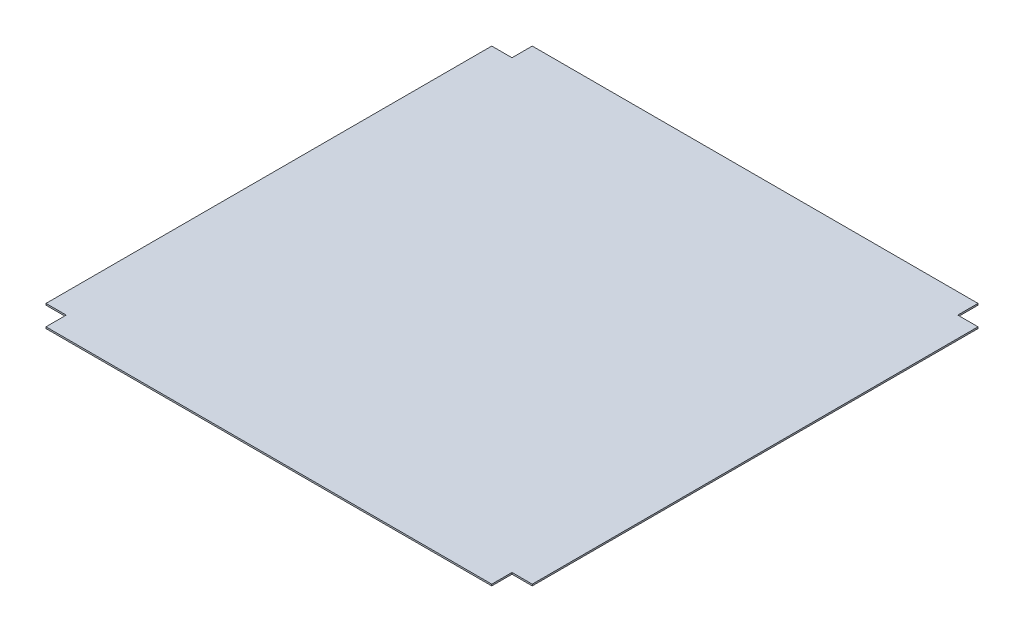
SolidWorks part; units mm, degrees
ref_plane "Front Plane" through (0, 0, 0) normal (0, 0, 1) x (1, 0, 0)
ref_plane "Top Plane" through (0, 0, 0) normal (0, 1, 0) x (1, 0, 0)
ref_plane "Right Plane" through (0, 0, 0) normal (1, 0, 0) x (0, 0, -1)
sketch "Sketch1" plane through (0, 0, 0) normal (0, 1, 0) x (1, 0, 0)
  line L1 (-609.6, -609.6) -> (609.6, -609.6)
  line L2 (-609.6, -609.6) -> (-609.6, 609.6)
  line L3 (-609.6, 609.6) -> (609.6, 609.6)
  line L4 (609.6, -609.6) -> (609.6, 609.6)
  line L5 (-609.6, -609.6) -> (609.6, 609.6) construction
  line L6 (-609.6, 609.6) -> (609.6, -609.6) construction
  point P0 (0, 0)
  dimension "D2" = 1219.2
  dimension "D1" = 1219.2
extrude "Boss-Extrude1" add sketch "Sketch1" along normal mid plane 4
sketch "Sketch2" plane through (0, 2, 0) normal (0, 1, 0) x (1, 0, 0)
  line L0 (0, 609.6) -> (0, -609.6) construction
  line L1 (-609.6, 609.6) -> (-558.8, 609.6)
  line L2 (-609.6, 609.6) -> (-609.6, 558.8)
  line L3 (-609.6, 558.8) -> (-558.8, 558.8)
  line L4 (-558.8, 609.6) -> (-558.8, 558.8)
  line L5 (609.6, 609.6) -> (-609.6, 609.6) construction
  line L6 (-609.6, -609.6) -> (609.6, -609.6) construction
  line L7 (609.6, 0) -> (-609.6, 0) construction
  line L8 (609.6, -609.6) -> (609.6, 609.6) construction
  line L9 (-609.6, 609.6) -> (-609.6, -609.6) construction
  line L10 (558.8, 609.6) -> (558.8, 558.8)
  line L11 (609.6, 558.8) -> (558.8, 558.8)
  line L12 (609.6, 609.6) -> (609.6, 558.8)
  line L13 (609.6, 609.6) -> (558.8, 609.6)
  line L14 (609.6, -609.6) -> (558.8, -609.6)
  line L15 (609.6, -609.6) -> (609.6, -558.8)
  line L16 (609.6, -558.8) -> (558.8, -558.8)
  line L17 (558.8, -609.6) -> (558.8, -558.8)
  line L18 (-558.8, -609.6) -> (-558.8, -558.8)
  line L19 (-609.6, -558.8) -> (-558.8, -558.8)
  line L20 (-609.6, -609.6) -> (-609.6, -558.8)
  line L21 (-609.6, -609.6) -> (-558.8, -609.6)
  dimension "D1" = 50.8
extrude "Cut-Extrude1" cut sketch "Sketch2" against normal through all
equation "\"width\"= 48in"
equation "\"length\"= 48in"
equation "\"square tubing width\"= 2in"
equation "\"D1@Sketch2\"=\"square tubing width\""
equation "\"D1@Sketch1\"=\"width\""
equation "\"D2@Sketch1\"=\"length\""
